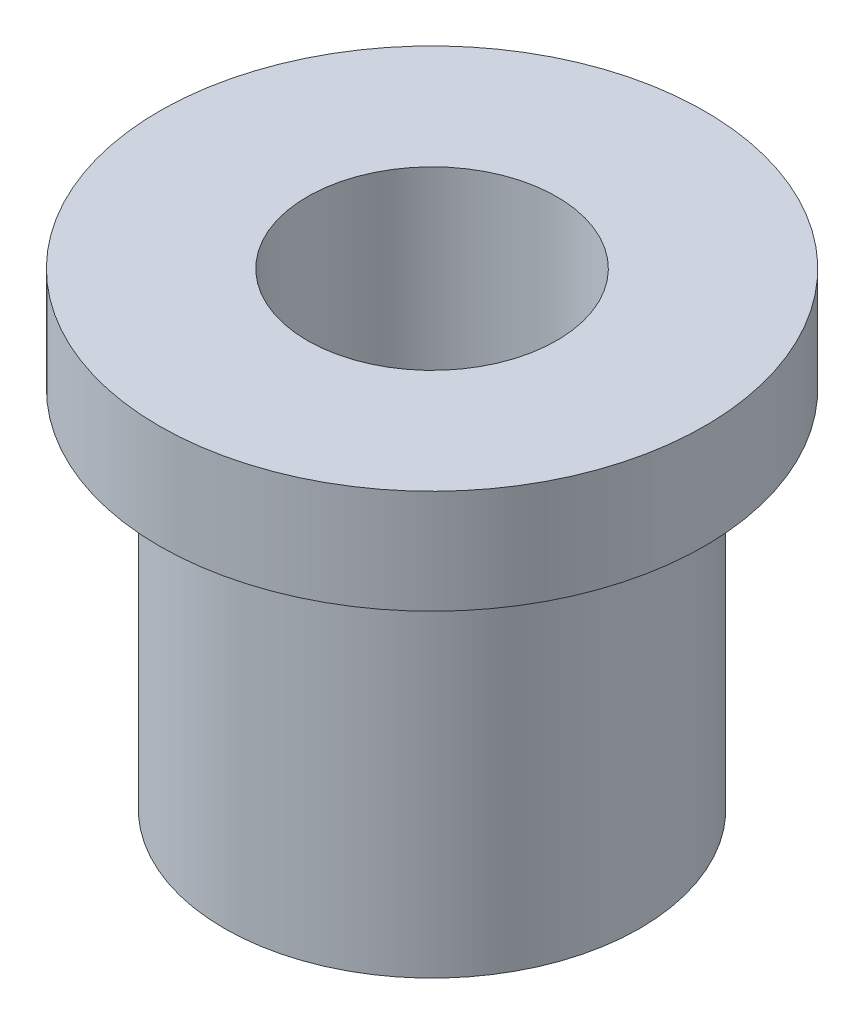
SolidWorks part; units mm, degrees
ref_plane "Front Plane" through (0, 0, 0) normal (0, 0, 1) x (1, 0, 0)
ref_plane "Top Plane" through (0, 0, 0) normal (0, 1, 0) x (1, 0, 0)
ref_plane "Right Plane" through (0, 0, 0) normal (1, 0, 0) x (0, 0, -1)
sketch "Sketch1" plane through (0, 0, 0) normal (0, 1, 0) x (1, 0, 0)
  circle A0 centre (0, 0) radius 2.4
  circle A1 centre (0, 0) radius 4
  dimension "D1" = 8
  dimension "D2" = 4.8
extrude "Boss-Extrude1" add sketch "Sketch1" along normal blind 9
sketch "Sketch2" plane through (0, 9, 0) normal (0, 1, 0) x (1, 0, 0)
  circle A0 centre (0, 0) radius 5.25
  circle A1 centre (0, 0) radius 2.4
  dimension "D1" = 10.5
extrude "Boss-Extrude2" add sketch "Sketch2" against normal blind 2
